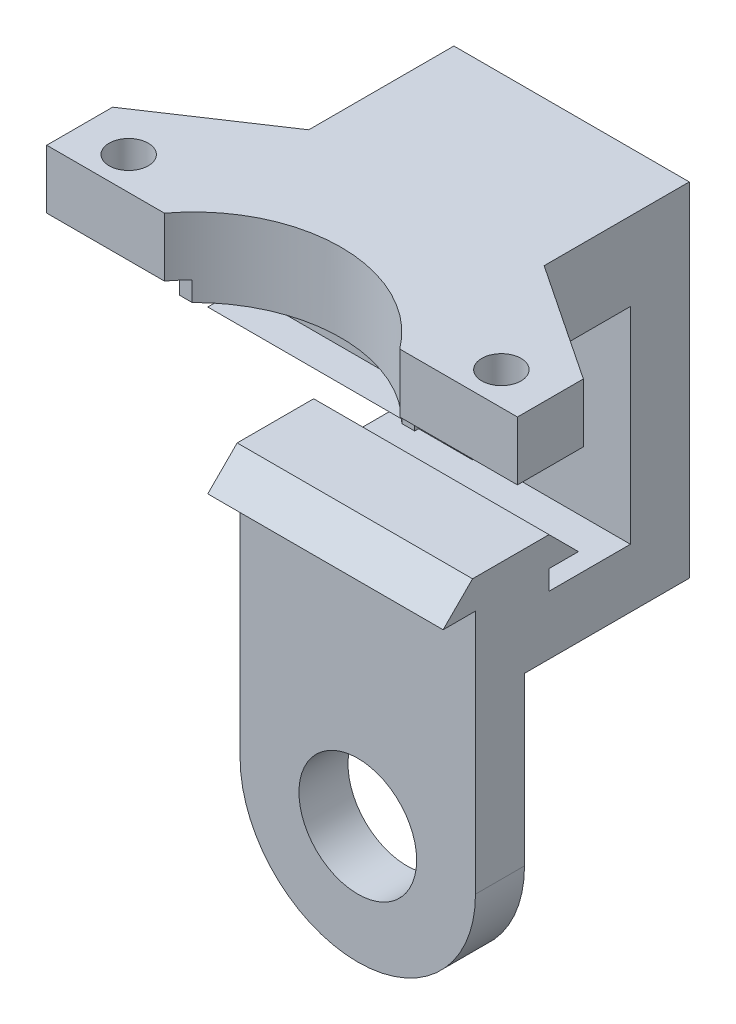
SolidWorks part; units mm, degrees
ref_plane "Plano frontal" through (0, 0, 0) normal (0, 0, 1) x (1, 0, 0)
ref_plane "Plano superior" through (0, 0, 0) normal (0, 1, 0) x (1, 0, 0)
ref_plane "Plano direito" through (0, 0, 0) normal (1, 0, 0) x (0, 0, -1)
sketch "Esboço1" plane through (0, 0, 0) normal (0, 0, 1) x (1, 0, 0)
  line L2 (-12, 0) -> (-12, 17)
  line L3 (-12, 17) -> (12, 17)
  line L4 (12, 0) -> (12, 17)
  circle A0 centre (0, 0) radius 6
  arc A1 (-12, 0) -> (12, 0) centre (0, 0) ccw
  dimension "D1" = 6
extrude "Ressalto-extrusão1" add sketch "Esboço1" along normal blind 5
sketch "Esboço2" plane through (-12, 0, 0) normal (-1, 0, 0) x (0, 0, 1)
  line L1 (5, 17) -> (0.2, 17)
  line L2 (5, 17) -> (5, 25)
  line L3 (-10.8, 44) -> (-2.5, 44)
  line L4 (11.2, 52) -> (11.2, 44)
  line L5 (-16.8, 52) -> (11.2, 52)
  line L6 (11.2, 44) -> (5, 44)
  line L7 (5.3, 28) -> (-2.5, 28)
  line L8 (-2.5, 23) -> (-2.5, 25)
  line L9 (0.2, 17) -> (-10.8, 17)
  line L10 (-2.5, 28) -> (-5.5, 25)
  line L11 (-2.5, 23) -> (-10.8, 23)
  line L12 (-5.5, 25) -> (-2.5, 25)
  line L13 (-10.8, 17) -> (-16.8, 17)
  line L14 (-10.8, 23) -> (-10.8, 44)
  line L16 (-16.8, 17) -> (-16.8, 52)
  line L17 (-2.5, 38.5) -> (-5.5, 41.5)
  line L18 (-5.5, 41.5) -> (-2.5, 41.5)
  line L19 (-2.5, 44) -> (-2.5, 41.5)
  line L20 (5.3, 28) -> (8.3, 25)
  line L21 (8.3, 25) -> (5, 25)
  line L23 (8.3, 41.5) -> (5, 41.5)
  line L24 (5.3, 38.5) -> (8.3, 41.5)
  line L25 (5.3, 38.5) -> (-2.5, 38.5)
  line L26 (5, 41.5) -> (5, 44)
  point P27 (-4.3, 39.5)
  point P31 (-2.8, 42)
  point P35 (4.8648, 43)
  dimension "D1" = 5
  dimension "D2" = 7.8
  dimension "D3" = 21
  dimension "D4" = 6
  dimension "D5" = 8
  dimension "D6" = 16.5
  dimension "D7" = 16.5
  dimension "D8" = 0
  dimension "D9" = 7.5
  dimension "D10" = 2
  dimension "D11" = 0
  dimension "D12" = 7.5
extrude "Ressalto-extrusão2" add sketch "Esboço2" against normal up to surface (24 mm away) up to face at (12, 8.5, 2.5)
sketch "Esboço3" plane through (0, 52, 0) normal (0, 1, 0) x (1, 0, 0)
  line L0 (12, -6) -> (-12, -6)
  line L1 (12, -12.72) -> (24, -12.72)
  line L3 (12, -11.2) -> (12, -12.72) construction
  line L4 (-12, -6) -> (-12, 2) construction
  line L5 (-12, -11.2) -> (-12, -12.72) construction
  line L6 (-12, -11.2) -> (-12, 16.8) construction
  line L7 (-12, 2) -> (-24, -6)
  line L8 (19, -9.36) -> (-19, -9.36) construction
  line L9 (0, -6) -> (0, -12.72) construction
  line L10 (24, -12.72) -> (24, -6)
  line L11 (-24, -12.72) -> (-12, -12.72)
  line L12 (-24, -6) -> (-24, -12.72)
  line L13 (24, -6) -> (12, 2)
  line L14 (12, 16.8) -> (12, -11.2) construction
  line L15 (12, 2) -> (12, -6)
  line L17 (-12, 2) -> (-12, -6)
  arc A0 (12, -12.72) -> (-12, -12.72) centre (0, -21.72) ccw
  circle A2 centre (19, -9.36) radius 2
  circle A3 centre (-19, -9.36) radius 2
  point P5 (0, -6)
  point P26 (0, -9.36)
extrude "Ressalto-extrusão3" add sketch "Esboço3" against normal blind 6
sketch "Esboço5" plane through (0, 52, 0) normal (0, 1, 0) x (1, 0, 0)
  circle A1 centre (0, -21.72) radius 15
extrude "Corte-extrusão1" cut sketch "Esboço5" against normal blind 10
